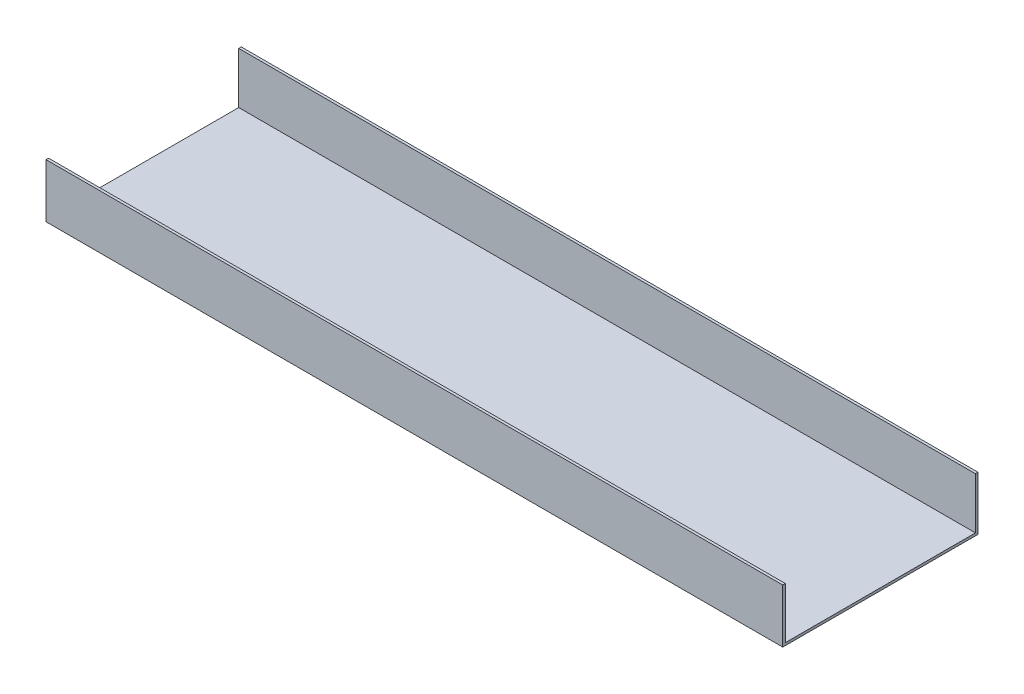
SolidWorks part; units mm, degrees
ref_plane "Front Plane" through (0, 0, 0) normal (0, 0, 1) x (1, 0, 0)
ref_plane "Top Plane" through (0, 0, 0) normal (0, 1, 0) x (1, 0, 0)
ref_plane "Right Plane" through (0, 0, 0) normal (1, 0, 0) x (0, 0, -1)
sketch "Sketch1" plane through (0, 0, 0) normal (0, 1, 0) x (1, 0, 0)
  line L1 (-143.75, 38.1) -> (143.75, 38.1)
  line L2 (-143.75, 38.1) -> (-143.75, -38.1)
  line L3 (-143.75, -38.1) -> (143.75, -38.1)
  line L4 (143.75, 38.1) -> (143.75, -38.1)
  line L5 (-143.75, 38.1) -> (143.75, -38.1) construction
  line L6 (-143.75, -38.1) -> (143.75, 38.1) construction
  point P0 (0, 0)
  dimension "D1" = 287.5
  dimension "D2" = 76.2
extrude "Boss-Extrude1" add sketch "Sketch1" along normal blind 1
sketch "Sketch2" plane through (0, 1, 0) normal (0, 1, 0) x (1, 0, 0)
  line L0 (-143.75, -37.1) -> (143.75, -37.1)
  line L1 (-143.75, 38.1) -> (-143.75, -38.1) construction
  line L2 (143.75, -38.1) -> (143.75, 38.1) construction
  line L3 (-143.75, 37.1) -> (143.75, 37.1)
  line L4 (-143.75, -38.1) -> (143.75, -38.1) construction
  line L5 (143.75, 38.1) -> (-143.75, 38.1) construction
  dimension "D1" = 1
  dimension "D2" = 1
extrude "Extrude-Thin1" add sketch "Sketch2" along normal blind 20 thin contours L0
sketch "Sketch5" plane through (0, 1, 0) normal (0, 1, 0) x (1, 0, 0)
  line L0 (-143.75, 37.1) -> (143.75, 37.1)
  line L1 (-143.75, 38.1) -> (-143.75, -37.1) construction
  line L2 (143.75, -37.1) -> (143.75, 38.1) construction
  line L3 (143.75, 38.1) -> (-143.75, 38.1) construction
  dimension "D1" = 1
extrude "Extrude-Thin2" add sketch "Sketch5" along normal blind 20 thin thin type one direction reverse wall 1
